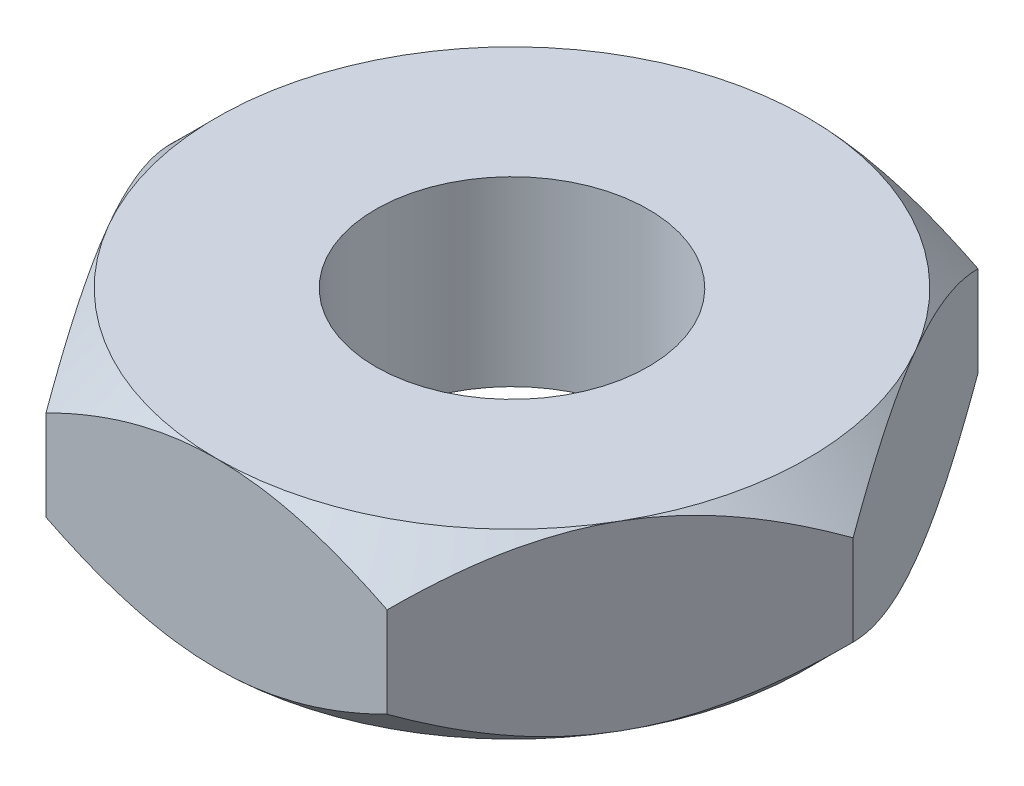
SolidWorks part; units mm, degrees
material "AISI 1045 Steel, cold drawn"
ref_plane "Front Plane" through (0, 0, 0) normal (0, 0, 1) x (1, 0, 0)
ref_plane "Top Plane" through (0, 0, 0) normal (0, 1, 0) x (1, 0, 0)
ref_plane "Right Plane" through (0, 0, 0) normal (1, 0, 0) x (0, 0, -1)
sketch "Sketch1" plane through (0, 0, 0) normal (0, 1, 0) x (1, 0, 0)
  line L1 (-15.0111, 0) -> (-7.5056, -13)
  line L2 (-7.5056, -13) -> (7.5056, -13)
  line L3 (7.5056, -13) -> (15.0111, 0)
  line L4 (15.0111, 0) -> (7.5056, 13)
  line L5 (7.5056, 13) -> (-7.5056, 13)
  line L6 (-7.5056, 13) -> (-15.0111, 0)
  circle A0 centre (0, 0) radius 13 construction
  circle A1 centre (0, 0) radius 6
  dimension "D1" = 26
  dimension "D2" = 12
extrude "Boss-Extrude1" add sketch "Sketch1" along normal blind 8
sketch "Sketch2" plane through (0, 8, 0) normal (0, 1, 0) x (1, 0, 0)
  circle A0 centre (0, 0) radius 13
  dimension "D1" = 26
extrude "Cut-Extrude1" cut sketch "Sketch2" against normal through all draft 45 flip side to cut contours A0
sketch "Sketch5" plane through (0, 0, 0) normal (0, -1, 0) x (-1, 0, 0)
  circle A0 centre (0, 0) radius 13
  dimension "D1" = 26
extrude "Cut-Extrude2" cut sketch "Sketch5" against normal through all draft 45 flip side to cut
